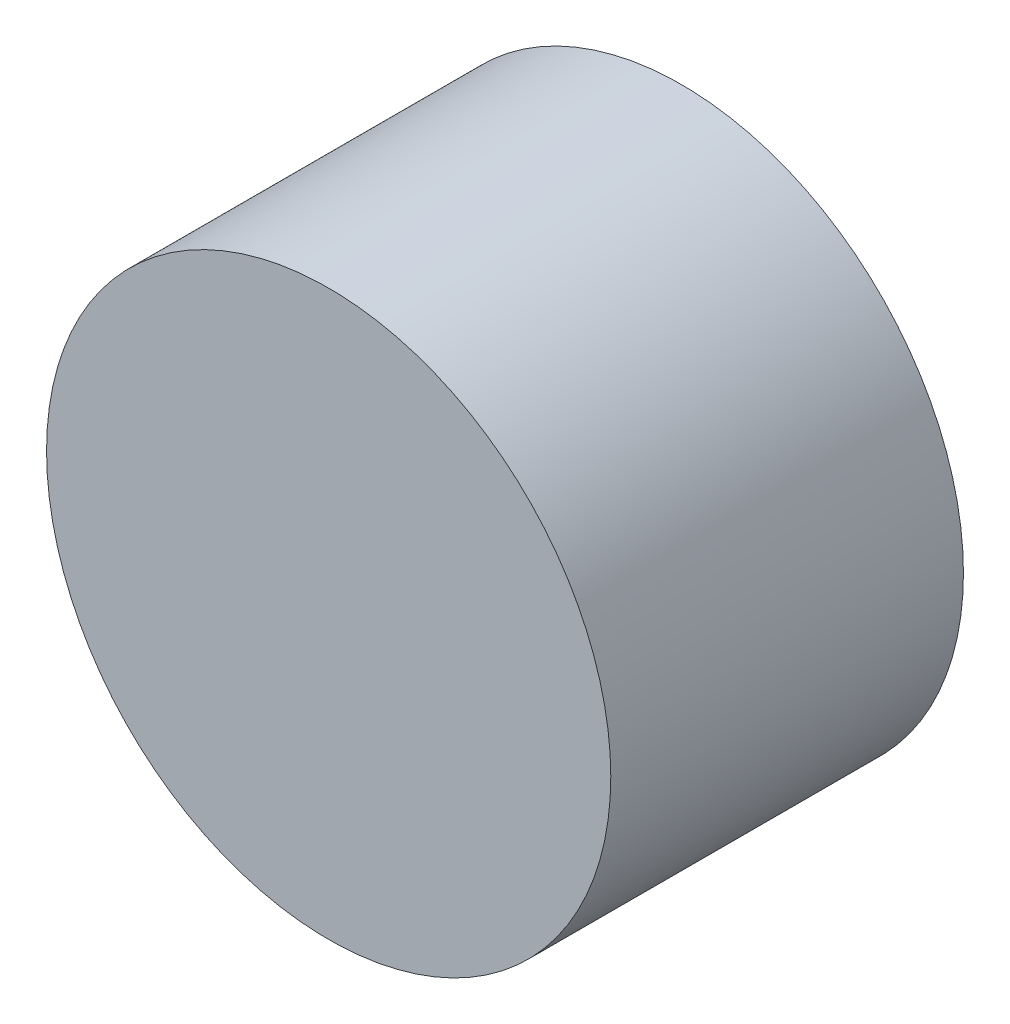
SolidWorks part; units mm, degrees
ref_plane "Front Plane" through (0, 0, 0) normal (0, 0, 1) x (1, 0, 0)
ref_plane "Top Plane" through (0, 0, 0) normal (0, 1, 0) x (1, 0, 0)
ref_plane "Right Plane" through (0, 0, 0) normal (1, 0, 0) x (0, 0, -1)
sketch "Sketch1" plane through (0, 0, 0) normal (0, 0, 1) x (1, 0, 0)
  circle A0 centre (0, 0) radius 4
  dimension "D1" = 8
extrude "Boss-Extrude1" add sketch "Sketch1" along normal blind 5
